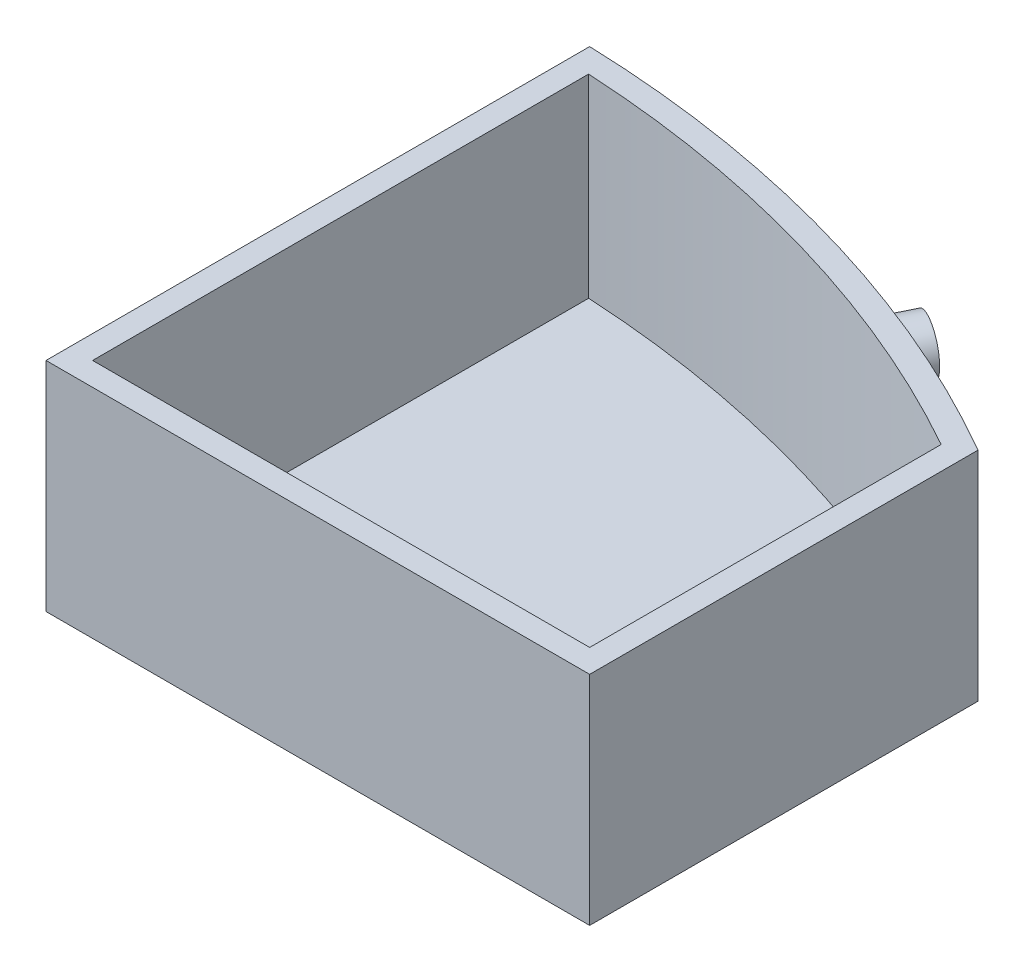
SolidWorks part; units mm, degrees
ref_plane "Front Plane" through (0, 0, 0) normal (0, 0, 1) x (1, 0, 0)
ref_plane "Top Plane" through (0, 0, 0) normal (0, 1, 0) x (1, 0, 0)
ref_plane "Right Plane" through (0, 0, 0) normal (1, 0, 0) x (0, 0, -1)
sketch "Sketch1" plane through (0, 0, 0) normal (0, 1, 0) x (1, 0, 0)
  line L0 (0, 0) -> (0, -70)
  line L1 (0, -70) -> (70, -70)
  line L2 (70, -70) -> (70, -20)
  arc A0 (0, 0) -> (70, -20) centre (-4.9764, -149.9174) cw
  dimension "D1" = 300
  dimension "D2" = 70
  dimension "D3" = 70
  dimension "D4" = 50
extrude "Boss-Extrude2" add sketch "Sketch1" along normal blind 3
sketch "Sketch3" plane through (0, 3, 0) normal (0, 1, 0) x (1, 0, 0)
  line L3 (70, -70) -> (70, -20) construction
  line L4 (0, -70) -> (70, -70) construction
  line L5 (0, 0) -> (0, -70) construction
  line L6 (3, -3.134) -> (3, -67)
  line L7 (3, -67) -> (67, -67)
  line L8 (67, -67) -> (67, -21.7441)
  line L9 (3, -3.134) -> (3, -67)
  line L10 (3, -67) -> (67, -67)
  line L11 (67, -67) -> (67, -21.7441)
  line L12 (70, -70) -> (70, -20)
  line L13 (0, -70) -> (70, -70)
  line L14 (0, 0) -> (0, -70)
  arc A1 (70, -20) -> (0, 0) centre (-4.9764, -149.9174) ccw construction
  arc A2 (67, -21.7441) -> (3, -3.134) centre (-4.9764, -149.9174) ccw
  arc A3 (67, -21.7441) -> (3, -3.134) centre (-4.9764, -149.9174) ccw
  arc A4 (70, -20) -> (0, 0) centre (-4.9764, -149.9174) ccw
  dimension "D1" = 3
extrude "Boss-Extrude3" add sketch "Sketch3" along normal blind 25
ref_plane "Plane3" through (0, 14, 0) normal (0, -1, 0) x (-1, 0, 0)
sketch "Sketch10" plane through (0, 14, 0) normal (0, -1, 0) x (-1, 0, 0)
  arc A0 (0, 0) -> (-70, -20) centre (4.9764, -149.9174) ccw construction
  arc A1 (0, 0) -> (-70, -20) centre (4.9764, -149.9174) ccw
ref_point "Point1" parameters "D1"=10
ref_plane "Plane5" through (61.1787, 14, 15.2939) normal (0.441, 0, -0.8975) x (-0.8975, 0, -0.441)
sketch "Sketch11" plane through (61.1787, 14, 15.2939) normal (0.441, 0, -0.8975) x (-0.8975, 0, -0.441)
  line L0 (-9.9926, 0) -> (61.6524, 0) construction
  circle A0 centre (25.8299, 0) radius 3.5
  dimension "D1" = 7
extrude "Boss-Extrude5" add sketch "Sketch11" along normal blind 7 and the other way up to next
